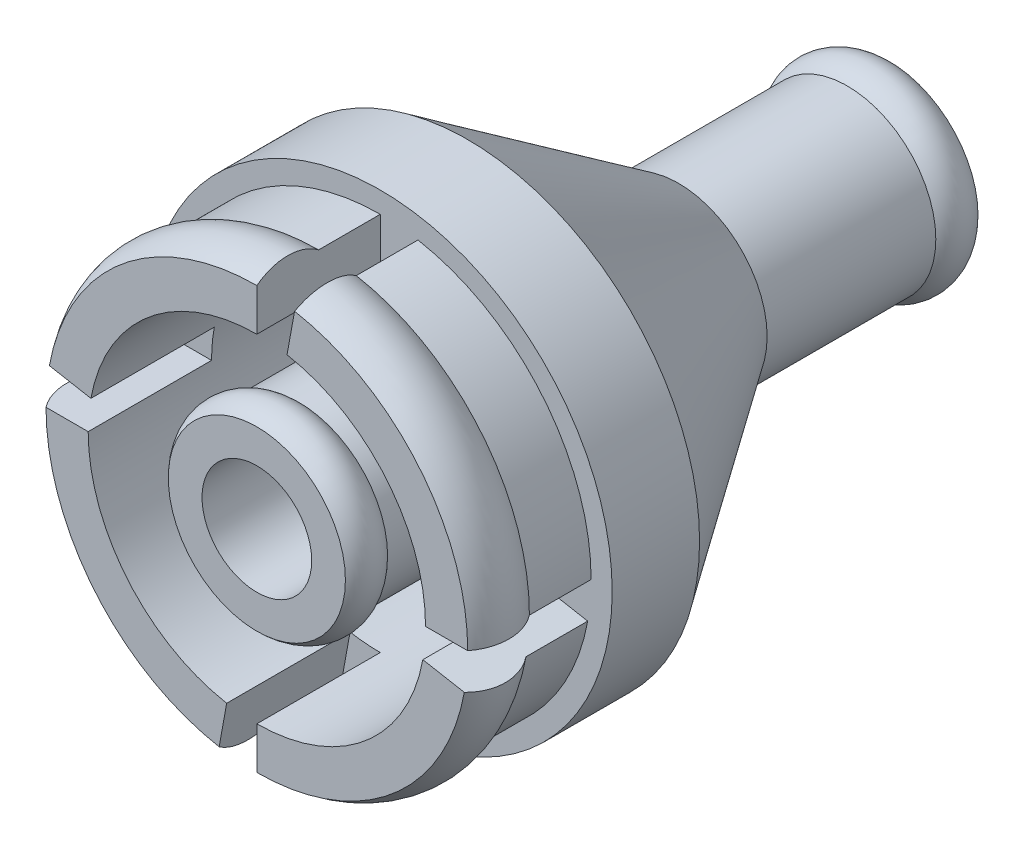
SolidWorks part; units mm, degrees
ref_plane "Front Plane" through (0, 0, 0) normal (0, 0, 1) x (1, 0, 0)
ref_plane "Top Plane" through (0, 0, 0) normal (0, 1, 0) x (1, 0, 0)
ref_plane "Right Plane" through (0, 0, 0) normal (1, 0, 0) x (0, 0, -1)
sketch "Sketch1" plane through (0, 0, 0) normal (0, 0, 1) x (1, 0, 0)
  circle A0 centre (0, 0) radius 1.3
  circle A1 centre (0, 0) radius 5.5
extrude "Boss-Extrude1" add sketch "Sketch1" along normal blind 15
ref_axis "Axis2" through (0, 0, 15) along (0, 0, -1)
sketch "Sketch3" plane through (0, 0, 0) normal (0, 1, 0) x (1, 0, 0)
  line L7 (-2.1, -5) -> (-5.5, -10.0019)
  line L12 (-5.5, 0) -> (-5.5, -10.0019)
  line L16 (-2.1, -1) -> (-2.1, -5)
  line L19 (-2.1, 0) -> (-5.5, 0)
  line L21 (-2.1, -15) -> (-4, -15)
  line L28 (-4, -15) -> (-4, -10)
  line L29 (-4, -10) -> (-2.1, -10)
  line L30 (-2.1, -10) -> (-2.1, -14)
  line L34 (-5.5, -15) -> (-5, -15)
  line L35 (-5.5, -15) -> (-5.5, -12.074)
  line L36 (-5.5, -12.074) -> (-5, -12.074)
  line L37 (-5, -13.537) -> (-5, -12.074)
  arc A4 (-2.1, -1) -> (-2.1, 0) centre (-1.6, -0.5) cw
  arc A5 (-2.1, -15) -> (-2.1, -14) centre (-1.6, -14.5) cw
  arc A7 (-5, -15) -> (-5, -13.537) centre (-4.0467, -14.2685) cw
revolve "Cut-Revolve1" cut sketch "Sketch3" angle 360 about axis through (0, 0, 15) along (0, 0, -1)
sketch "Sketch4" plane through (0, 0, 15) normal (0, 0, 1) x (1, 0, 0)
  line L0 (0, -4) -> (0, -5.5)
  line L4 (-4, 0) -> (-5.5, 0)
  line L6 (0, 4) -> (0, 5.5)
  line L10 (4, 0) -> (5.5, 0)
  line L17 (-0.9839, -5.4113) -> (-0.7155, -3.9355)
  line L19 (-5.4113, 0.9839) -> (-3.9355, 0.7155)
  line L21 (0.9839, 5.4113) -> (0.7155, 3.9355)
  line L23 (5.4113, -0.9839) -> (3.9355, -0.7155)
  arc A2 (-0.9839, -5.4113) -> (0, -5.5) centre (0, 0) ccw
  arc A4 (5.4113, -0.9839) -> (5.5, 0) centre (0, 0) ccw
  arc A7 (-5.4113, 0.9839) -> (-5.5, 0) centre (0, 0) ccw
  arc A8 (0.9839, 5.4113) -> (0, 5.5) centre (0, 0) ccw
  arc A10 (-0.7155, -3.9355) -> (0, -4) centre (0, 0) ccw
  arc A12 (-3.9355, 0.7155) -> (-4, 0) centre (0, 0) ccw
  arc A14 (0.7155, 3.9355) -> (0, 4) centre (0, 0) ccw
  arc A16 (3.9355, -0.7155) -> (4, 0) centre (0, 0) ccw
extrude "Cut-Extrude1" cut sketch "Sketch4" along direction (0, 0, 1) on the side against the normal up to surface (2.926 mm away)
